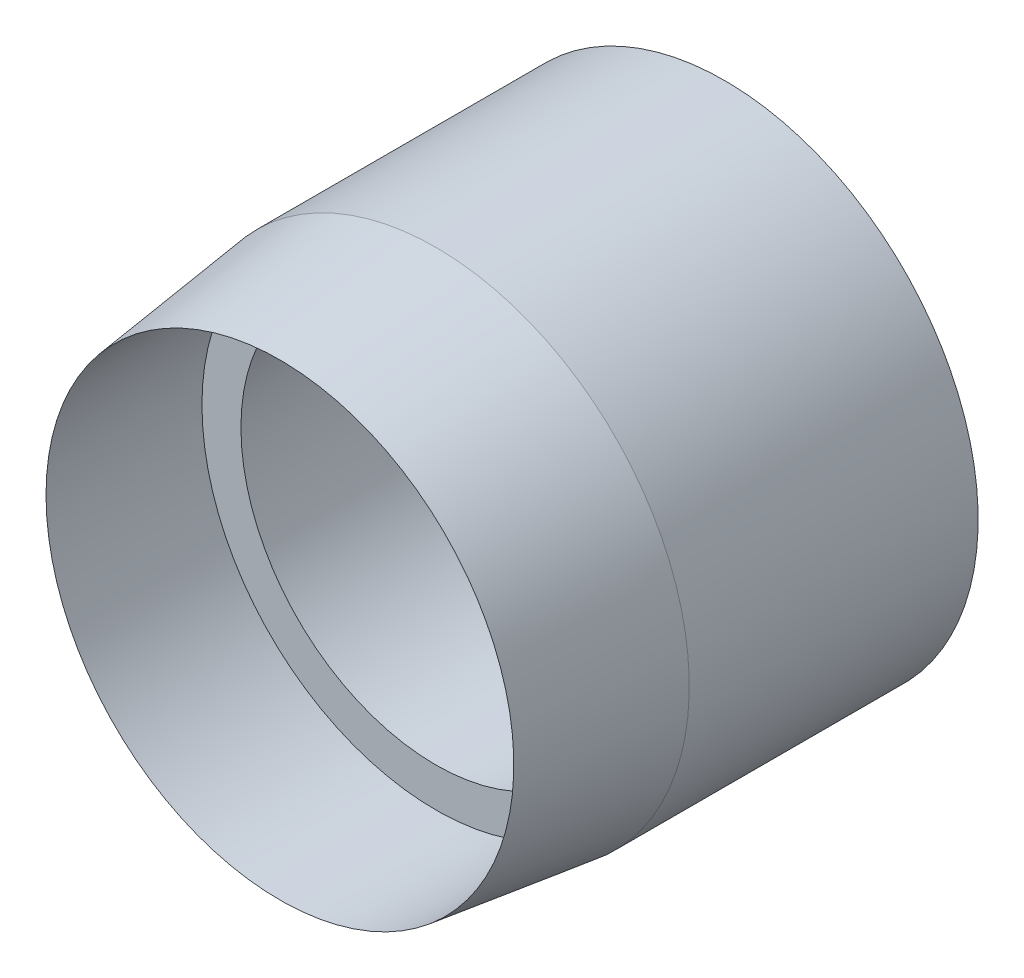
SolidWorks part; units mm, degrees
ref_plane "Front Plane" through (0, 0, 0) normal (1, 0, 0) x (0, 1, 0)
ref_plane "Top Plane" through (0, 0, 0) normal (0, 0, 1) x (0, 1, 0)
ref_plane "Right Plane" through (0, 0, 0) normal (0, 1, 0) x (-1, 0, 0)
sketch "Sketch1" plane through (0, 0, 0) normal (1, 0, 0) x (0, 1, 0)
  line L0 (-63.5, 0) -> (-82.55, 0)
  line L5 (-76.2, 94.1086) -> (-63.5, 94.1086)
  line L6 (-63.5, 0) -> (-63.5, 94.1086)
  line L7 (0, 0) -> (0, 100.9873) construction
  line L10 (-82.55, 94.1086) -> (-76.2, 144.9086)
  line L11 (-76.2, 144.9086) -> (-76.2, 94.1086)
  line L12 (-82.55, 94.1086) -> (-82.55, 0)
  point P3 (-82.0009, 0)
  point P4 (-82.0009, 108.5205)
  point P6 (-82.55, 94.1086)
  dimension "D1" = 63.5
  dimension "D2" = 82.55
  dimension "D3" = 6.35
  dimension "D4" = 94.1086
  dimension "D5" = 50.8
revolve "Revolve1" add sketch "Sketch1" angle 360 about L7
